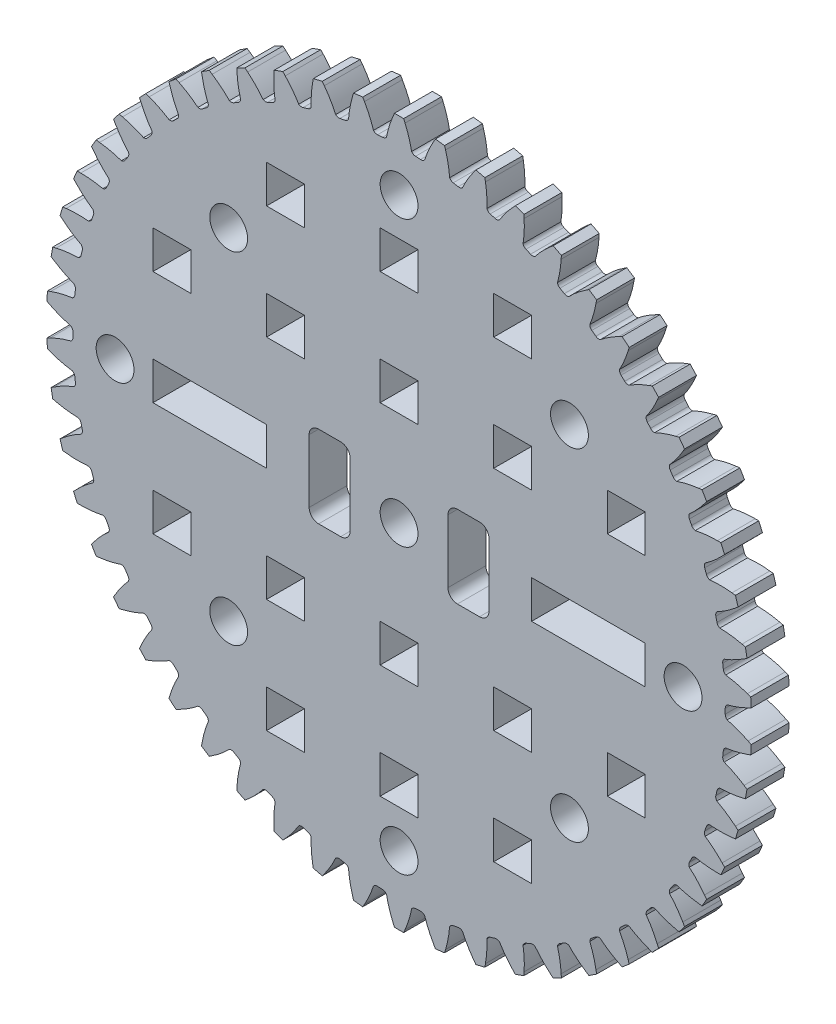
SolidWorks part; units mm, degrees
ref_plane "Alzado" through (0, 0, 0) normal (0, 0, 1) x (1, 0, 0)
ref_plane "Planta" through (0, 0, 0) normal (0, 1, 0) x (1, 0, 0)
ref_plane "Vista lateral" through (0, 0, 0) normal (1, 0, 0) x (0, 0, -1)
sketch "Model" plane through (0, 0, 0) normal (0, 0, 1) x (1, 0, 0)
  line L0 (26.2461, 285.5829) -> (26.2461, 282.5829)
  line L1 (29.2461, 285.5829) -> (26.2461, 285.5829)
  line L2 (29.2461, 282.5829) -> (29.2461, 285.5829)
  line L3 (26.2461, 282.5829) -> (29.2461, 282.5829)
  line L4 (35.2461, 285.5829) -> (35.2461, 282.5829)
  line L5 (38.2461, 285.5829) -> (35.2461, 285.5829)
  line L6 (38.2461, 282.5829) -> (38.2461, 285.5829)
  line L7 (35.2461, 282.5829) -> (38.2461, 282.5829)
  line L8 (44.2461, 285.5829) -> (44.2461, 282.5829)
  line L9 (47.2461, 285.5829) -> (44.2461, 285.5829)
  line L10 (47.2461, 282.5829) -> (47.2461, 285.5829)
  line L11 (44.2461, 282.5829) -> (47.2461, 282.5829)
  line L12 (56.2461, 258.5829) -> (53.2461, 258.5829)
  line L13 (56.2461, 255.5829) -> (56.2461, 258.5829)
  line L14 (53.2461, 255.5829) -> (56.2461, 255.5829)
  line L15 (53.2461, 258.5829) -> (53.2461, 255.5829)
  line L16 (56.2461, 276.5829) -> (53.2461, 276.5829)
  line L17 (56.2461, 273.5829) -> (56.2461, 276.5829)
  line L18 (53.2461, 273.5829) -> (56.2461, 273.5829)
  line L19 (53.2461, 276.5829) -> (53.2461, 273.5829)
  line L20 (47.2461, 267.5829) -> (47.2461, 264.5829)
  line L21 (26.2461, 276.5829) -> (26.2461, 273.5829)
  line L22 (29.2461, 276.5829) -> (26.2461, 276.5829)
  line L23 (29.2461, 273.5829) -> (29.2461, 276.5829)
  line L24 (26.2461, 273.5829) -> (29.2461, 273.5829)
  line L25 (35.2461, 276.5829) -> (35.2461, 273.5829)
  line L26 (38.2461, 276.5829) -> (35.2461, 276.5829)
  line L27 (38.2461, 273.5829) -> (38.2461, 276.5829)
  line L28 (35.2461, 273.5829) -> (38.2461, 273.5829)
  line L29 (44.2461, 276.5829) -> (44.2461, 273.5829)
  line L30 (47.2461, 276.5829) -> (44.2461, 276.5829)
  line L31 (47.2461, 273.5829) -> (47.2461, 276.5829)
  line L32 (44.2461, 273.5829) -> (47.2461, 273.5829)
  line L33 (26.2461, 258.5829) -> (26.2461, 255.5829)
  line L34 (29.2461, 258.5829) -> (26.2461, 258.5829)
  line L35 (29.2461, 255.5829) -> (29.2461, 258.5829)
  line L36 (26.2461, 255.5829) -> (29.2461, 255.5829)
  line L37 (35.2461, 258.5829) -> (35.2461, 255.5829)
  line L38 (38.2461, 258.5829) -> (35.2461, 258.5829)
  line L39 (38.2461, 255.5829) -> (38.2461, 258.5829)
  line L40 (35.2461, 255.5829) -> (38.2461, 255.5829)
  line L41 (44.2461, 258.5829) -> (44.2461, 255.5829)
  line L42 (47.2461, 258.5829) -> (44.2461, 258.5829)
  line L43 (47.2461, 255.5829) -> (47.2461, 258.5829)
  line L44 (44.2461, 255.5829) -> (47.2461, 255.5829)
  line L45 (26.2461, 249.5829) -> (26.2461, 246.5829)
  line L46 (29.2461, 249.5829) -> (26.2461, 249.5829)
  line L47 (29.2461, 246.5829) -> (29.2461, 249.5829)
  line L48 (26.2461, 246.5829) -> (29.2461, 246.5829)
  line L49 (35.2461, 249.5829) -> (35.2461, 246.5829)
  line L50 (38.2461, 249.5829) -> (35.2461, 249.5829)
  line L51 (38.2461, 246.5829) -> (38.2461, 249.5829)
  line L52 (35.2461, 246.5829) -> (38.2461, 246.5829)
  line L53 (44.2461, 249.5829) -> (44.2461, 246.5829)
  line L54 (47.2461, 249.5829) -> (44.2461, 249.5829)
  line L55 (47.2461, 246.5829) -> (47.2461, 249.5829)
  line L56 (44.2461, 246.5829) -> (47.2461, 246.5829)
  line L57 (20.2461, 258.5829) -> (17.2461, 258.5829)
  line L58 (20.2461, 255.5829) -> (20.2461, 258.5829)
  line L59 (17.2461, 255.5829) -> (20.2461, 255.5829)
  line L60 (17.2461, 258.5829) -> (17.2461, 255.5829)
  line L61 (20.2461, 276.5829) -> (17.2461, 276.5829)
  line L62 (20.2461, 273.5829) -> (20.2461, 276.5829)
  line L63 (17.2461, 273.5829) -> (20.2461, 273.5829)
  line L64 (17.2461, 276.5829) -> (17.2461, 273.5829)
  line L73 (56.2461, 267.5829) -> (47.2461, 267.5829)
  line L74 (56.2461, 264.5829) -> (56.2461, 267.5829)
  line L75 (47.2461, 264.5829) -> (56.2461, 264.5829)
  line L76 (17.2461, 267.5829) -> (17.2461, 264.5829)
  line L77 (26.2461, 267.5829) -> (17.2461, 267.5829)
  line L78 (26.2461, 264.5829) -> (26.2461, 267.5829)
  line L79 (17.2461, 264.5829) -> (26.2461, 264.5829)
  line L80 (43.1211, 269.3329) -> (41.3711, 269.3329)
  line L81 (43.8711, 263.5829) -> (43.8711, 268.5829)
  line L82 (41.3711, 262.8329) -> (43.1211, 262.8329)
  line L83 (40.6211, 268.5829) -> (40.6211, 263.5829)
  line L84 (30.3711, 269.3329) -> (32.1211, 269.3329)
  line L85 (29.6211, 263.5829) -> (29.6211, 268.5829)
  line L86 (32.1211, 262.8329) -> (30.3711, 262.8329)
  line L87 (32.8711, 268.5829) -> (32.8711, 263.5829)
  line L88 (42.6661, 293.1187) -> (42.8318, 293.3418)
  line L89 (42.8318, 293.3418) -> (43.5414, 293.1736)
  line L90 (43.5414, 293.1736) -> (43.5893, 292.8999)
  line L91 (43.967, 290.8966) -> (44.3484, 290.7824)
  line L92 (45.7647, 292.2486) -> (45.9552, 292.4509)
  line L93 (45.9552, 292.4509) -> (46.6405, 292.2015)
  line L94 (46.6405, 292.2015) -> (46.6563, 291.9241)
  line L95 (46.7989, 289.8905) -> (47.1644, 289.7328)
  line L96 (48.7414, 291.0247) -> (48.9541, 291.2035)
  line L97 (48.9541, 291.2035) -> (49.6058, 290.8762)
  line L98 (49.6058, 290.8762) -> (49.5893, 290.5988)
  line L99 (49.4948, 288.5625) -> (49.8396, 288.3634)
  line L100 (51.5559, 289.4634) -> (51.7879, 289.6164)
  line L101 (51.7879, 289.6164) -> (52.3971, 289.2157)
  line L102 (52.3971, 289.2157) -> (52.3486, 288.9421)
  line L103 (52.0183, 286.9304) -> (52.3376, 286.6927)
  line L104 (54.17, 287.586) -> (54.4182, 287.711)
  line L105 (54.4182, 287.711) -> (54.9769, 287.2423)
  line L106 (54.9769, 287.2423) -> (54.8969, 286.9762)
  line L107 (54.3353, 285.0165) -> (54.6249, 284.7433)
  line L108 (56.5486, 285.4178) -> (56.8096, 285.5132)
  line L109 (56.8096, 285.5132) -> (57.31, 284.9828)
  line L110 (57.31, 284.9828) -> (57.1997, 284.7277)
  line L111 (56.4144, 282.8465) -> (56.6703, 282.5415)
  line L112 (58.6593, 282.9882) -> (58.9297, 283.0526)
  line L113 (58.9297, 283.0526) -> (59.3651, 282.4676)
  line L114 (59.3651, 282.4676) -> (59.2259, 282.2271)
  line L115 (58.2276, 280.4497) -> (58.4463, 280.1172)
  line L116 (60.4738, 280.3299) -> (60.7497, 280.3624)
  line L117 (60.7497, 280.3624) -> (61.1143, 279.7309)
  line L118 (61.1143, 279.7309) -> (60.9482, 279.5082)
  line L119 (59.7502, 277.8588) -> (59.9289, 277.503)
  line L120 (61.9673, 277.4789) -> (62.2452, 277.4792)
  line L121 (62.2452, 277.4792) -> (62.534, 276.8097)
  line L122 (62.534, 276.8097) -> (62.3431, 276.6077)
  line L123 (60.9617, 275.1085) -> (61.0979, 274.7344)
  line L124 (63.1198, 274.4739) -> (63.3958, 274.4419)
  line L125 (63.3958, 274.4419) -> (63.6049, 273.7433)
  line L126 (63.6049, 273.7433) -> (63.3919, 273.5649)
  line L127 (61.8458, 272.2362) -> (61.9376, 271.8489)
  line L128 (63.9156, 271.3553) -> (64.186, 271.2916)
  line L129 (64.186, 271.2916) -> (64.3126, 270.5734)
  line L130 (64.3126, 270.5734) -> (64.0803, 270.421)
  line L131 (62.3905, 269.2807) -> (62.4367, 268.8853)
  line L132 (64.3439, 268.1655) -> (64.6052, 268.0707)
  line L133 (64.6052, 268.0707) -> (64.6476, 267.3428)
  line L134 (64.6476, 267.3428) -> (64.3991, 267.2183)
  line L135 (62.5883, 266.282) -> (62.5883, 265.8839)
  line L136 (64.3991, 264.9475) -> (64.6476, 264.8231)
  line L137 (64.6476, 264.8231) -> (64.6052, 264.0951)
  line L138 (64.6052, 264.0951) -> (64.3439, 264.0003)
  line L139 (62.4367, 263.2805) -> (62.3905, 262.8851)
  line L140 (64.0803, 261.7449) -> (64.3126, 261.5924)
  line L141 (64.3126, 261.5924) -> (64.186, 260.8743)
  line L142 (64.186, 260.8743) -> (63.9156, 260.8105)
  line L143 (61.9376, 260.317) -> (61.8458, 259.9296)
  line L144 (63.3919, 258.6009) -> (63.6049, 258.4225)
  line L145 (63.6049, 258.4225) -> (63.3958, 257.7239)
  line L146 (63.3958, 257.7239) -> (63.1198, 257.6919)
  line L147 (61.0979, 257.4314) -> (60.9617, 257.0573)
  line L148 (62.3431, 255.5581) -> (62.534, 255.3562)
  line L149 (62.534, 255.3562) -> (62.2452, 254.6866)
  line L150 (62.2452, 254.6866) -> (61.9673, 254.6869)
  line L151 (59.9289, 254.6628) -> (59.7502, 254.3071)
  line L152 (60.9482, 252.6576) -> (61.1143, 252.4349)
  line L153 (61.1143, 252.4349) -> (60.7497, 251.8034)
  line L154 (60.7497, 251.8034) -> (60.4738, 251.8359)
  line L155 (58.4463, 252.0487) -> (58.2276, 251.7161)
  line L156 (59.2259, 249.9387) -> (59.3651, 249.6982)
  line L157 (59.3651, 249.6982) -> (58.9297, 249.1133)
  line L158 (58.9297, 249.1133) -> (58.6593, 249.1776)
  line L159 (56.6703, 249.6243) -> (56.4144, 249.3194)
  line L160 (57.1997, 247.4381) -> (57.31, 247.1831)
  line L161 (57.31, 247.1831) -> (56.8096, 246.6527)
  line L162 (56.8096, 246.6527) -> (56.5486, 246.748)
  line L163 (54.6249, 247.4225) -> (54.3353, 247.1494)
  line L164 (54.8969, 245.1897) -> (54.9769, 244.9235)
  line L165 (54.9769, 244.9235) -> (54.4182, 244.4548)
  line L166 (54.4182, 244.4548) -> (54.17, 244.5798)
  line L167 (52.3376, 245.4731) -> (52.0183, 245.2354)
  line L168 (52.3486, 243.2238) -> (52.3971, 242.9501)
  line L169 (52.3971, 242.9501) -> (51.7879, 242.5494)
  line L170 (51.7879, 242.5494) -> (51.5559, 242.7024)
  line L171 (49.8396, 243.8024) -> (49.4948, 243.6034)
  line L172 (49.5893, 241.567) -> (49.6058, 241.2896)
  line L173 (49.6058, 241.2896) -> (48.9541, 240.9623)
  line L174 (48.9541, 240.9623) -> (48.7414, 241.1412)
  line L175 (47.1644, 242.433) -> (46.7989, 242.2753)
  line L176 (46.6563, 240.2417) -> (46.6405, 239.9643)
  line L177 (46.6405, 239.9643) -> (45.9552, 239.7149)
  line L178 (45.9552, 239.7149) -> (45.7647, 239.9172)
  line L179 (44.3484, 241.3834) -> (43.967, 241.2692)
  line L180 (43.5893, 239.266) -> (43.5414, 238.9922)
  line L181 (43.5414, 238.9922) -> (42.8318, 238.8241)
  line L182 (42.8318, 238.8241) -> (42.6661, 239.0471)
  line L183 (41.4295, 240.6678) -> (41.0375, 240.5987)
  line L184 (40.4298, 238.6528) -> (40.3504, 238.3865)
  line L185 (40.3504, 238.3865) -> (39.6261, 238.3019)
  line L186 (39.6261, 238.3019) -> (39.4874, 238.5427)
  line L187 (38.4474, 240.296) -> (38.05, 240.2728)
  line L188 (37.2205, 238.4106) -> (37.1107, 238.1554)
  line L189 (37.1107, 238.1554) -> (36.3815, 238.1554)
  line L190 (36.3815, 238.1554) -> (36.2717, 238.4106)
  line L191 (35.4422, 240.2728) -> (35.0448, 240.296)
  line L192 (34.0047, 238.5427) -> (33.866, 238.3019)
  line L193 (33.866, 238.3019) -> (33.1417, 238.3865)
  line L194 (33.1417, 238.3865) -> (33.0623, 238.6528)
  line L195 (32.4546, 240.5987) -> (32.0626, 240.6678)
  line L196 (30.826, 239.0471) -> (30.6603, 238.8241)
  line L197 (30.6603, 238.8241) -> (29.9507, 238.9922)
  line L198 (29.9507, 238.9922) -> (29.9028, 239.266)
  line L199 (29.5251, 241.2692) -> (29.1437, 241.3834)
  line L200 (27.7274, 239.9172) -> (27.5369, 239.7149)
  line L201 (27.5369, 239.7149) -> (26.8517, 239.9643)
  line L202 (26.8517, 239.9643) -> (26.8358, 240.2417)
  line L203 (26.6932, 242.2753) -> (26.3277, 242.433)
  line L204 (24.7507, 241.1412) -> (24.538, 240.9623)
  line L205 (24.538, 240.9623) -> (23.8864, 241.2896)
  line L206 (23.8864, 241.2896) -> (23.9028, 241.567)
  line L207 (23.9973, 243.6034) -> (23.6526, 243.8024)
  line L208 (21.9363, 242.7024) -> (21.7043, 242.5494)
  line L209 (21.7043, 242.5494) -> (21.095, 242.9501)
  line L210 (21.095, 242.9501) -> (21.1435, 243.2238)
  line L211 (19.3221, 244.5798) -> (19.0739, 244.4548)
  line L212 (19.0739, 244.4548) -> (18.5153, 244.9235)
  line L213 (18.5153, 244.9235) -> (18.5953, 245.1897)
  line L214 (19.1568, 247.1494) -> (18.8673, 247.4225)
  line L215 (16.9435, 246.748) -> (16.6825, 246.6527)
  line L216 (16.6825, 246.6527) -> (16.1821, 247.1831)
  line L217 (16.1821, 247.1831) -> (16.2924, 247.4381)
  line L218 (17.0777, 249.3194) -> (16.8218, 249.6243)
  line L219 (14.8328, 249.1776) -> (14.5625, 249.1133)
  line L220 (14.5625, 249.1133) -> (14.127, 249.6982)
  line L221 (14.127, 249.6982) -> (14.2662, 249.9387)
  line L222 (15.2646, 251.7161) -> (15.0458, 252.0487)
  line L223 (13.0184, 251.8359) -> (12.7424, 251.8034)
  line L224 (12.7424, 251.8034) -> (12.3778, 252.4349)
  line L225 (12.3778, 252.4349) -> (12.544, 252.6576)
  line L226 (13.7419, 254.3071) -> (13.5633, 254.6628)
  line L227 (11.5248, 254.6869) -> (11.2469, 254.6866)
  line L228 (11.2469, 254.6866) -> (10.9581, 255.3562)
  line L229 (10.9581, 255.3562) -> (11.149, 255.5581)
  line L230 (12.5304, 257.0573) -> (12.3942, 257.4314)
  line L231 (10.3724, 257.6919) -> (10.0963, 257.7239)
  line L232 (10.0963, 257.7239) -> (9.8872, 258.4225)
  line L233 (9.8872, 258.4225) -> (10.1003, 258.6009)
  line L234 (11.6463, 259.9296) -> (11.5545, 260.317)
  line L235 (9.5766, 260.8105) -> (9.3061, 260.8743)
  line L236 (9.3061, 260.8743) -> (9.1795, 261.5924)
  line L237 (9.1795, 261.5924) -> (9.4118, 261.7449)
  line L238 (11.1017, 262.8851) -> (11.0555, 263.2805)
  line L239 (9.1482, 264.0003) -> (8.887, 264.0951)
  line L240 (8.887, 264.0951) -> (8.8446, 264.8231)
  line L241 (8.8446, 264.8231) -> (9.093, 264.9475)
  line L242 (10.9038, 265.8839) -> (10.9038, 266.282)
  line L243 (9.093, 267.2183) -> (8.8446, 267.3428)
  line L244 (8.8446, 267.3428) -> (8.887, 268.0707)
  line L245 (8.887, 268.0707) -> (9.1482, 268.1655)
  line L246 (11.0555, 268.8853) -> (11.1017, 269.2807)
  line L247 (9.4118, 270.421) -> (9.1795, 270.5734)
  line L248 (9.1795, 270.5734) -> (9.3061, 271.2916)
  line L249 (9.3061, 271.2916) -> (9.5766, 271.3553)
  line L250 (11.5545, 271.8489) -> (11.6463, 272.2362)
  line L251 (10.1003, 273.5649) -> (9.8872, 273.7433)
  line L252 (9.8872, 273.7433) -> (10.0963, 274.4419)
  line L253 (10.0963, 274.4419) -> (10.3724, 274.4739)
  line L254 (12.3942, 274.7344) -> (12.5304, 275.1085)
  line L255 (11.149, 276.6077) -> (10.9581, 276.8097)
  line L256 (10.9581, 276.8097) -> (11.2469, 277.4792)
  line L257 (11.2469, 277.4792) -> (11.5248, 277.4789)
  line L258 (13.5633, 277.503) -> (13.7419, 277.8588)
  line L259 (12.544, 279.5082) -> (12.3778, 279.7309)
  line L260 (12.3778, 279.7309) -> (12.7424, 280.3624)
  line L261 (12.7424, 280.3624) -> (13.0184, 280.3299)
  line L262 (15.0458, 280.1172) -> (15.2646, 280.4497)
  line L263 (14.2662, 282.2271) -> (14.127, 282.4676)
  line L264 (14.127, 282.4676) -> (14.5625, 283.0526)
  line L265 (14.5625, 283.0526) -> (14.8328, 282.9882)
  line L266 (16.8218, 282.5415) -> (17.0777, 282.8465)
  line L267 (16.2924, 284.7277) -> (16.1821, 284.9828)
  line L268 (16.1821, 284.9828) -> (16.6825, 285.5132)
  line L269 (16.6825, 285.5132) -> (16.9435, 285.4178)
  line L270 (18.8673, 284.7433) -> (19.1568, 285.0165)
  line L271 (18.5953, 286.9762) -> (18.5153, 287.2423)
  line L272 (18.5153, 287.2423) -> (19.0739, 287.711)
  line L273 (19.0739, 287.711) -> (19.3221, 287.586)
  line L274 (21.1545, 286.6927) -> (21.4738, 286.9304)
  line L275 (21.1435, 288.9421) -> (21.095, 289.2157)
  line L276 (21.095, 289.2157) -> (21.7043, 289.6164)
  line L277 (21.7043, 289.6164) -> (21.9363, 289.4634)
  line L278 (23.6526, 288.3634) -> (23.9973, 288.5625)
  line L279 (23.9028, 290.5988) -> (23.8864, 290.8762)
  line L280 (23.8864, 290.8762) -> (24.538, 291.2035)
  line L281 (24.538, 291.2035) -> (24.7507, 291.0247)
  line L282 (26.3277, 289.7328) -> (26.6932, 289.8905)
  line L283 (26.8358, 291.9241) -> (26.8517, 292.2015)
  line L284 (26.8517, 292.2015) -> (27.5369, 292.4509)
  line L285 (27.5369, 292.4509) -> (27.7274, 292.2486)
  line L286 (29.1437, 290.7824) -> (29.5251, 290.8966)
  line L287 (29.9028, 292.8999) -> (29.9507, 293.1736)
  line L288 (29.9507, 293.1736) -> (30.6603, 293.3418)
  line L289 (30.6603, 293.3418) -> (30.826, 293.1187)
  line L290 (32.0626, 291.498) -> (32.4546, 291.5671)
  line L291 (33.0623, 293.513) -> (33.1417, 293.7793)
  line L292 (33.1417, 293.7793) -> (33.866, 293.864)
  line L293 (33.866, 293.864) -> (34.0047, 293.6231)
  line L294 (35.0448, 291.8699) -> (35.4422, 291.893)
  line L295 (38.05, 291.893) -> (38.4474, 291.8699)
  line L296 (39.4874, 293.6231) -> (39.6261, 293.864)
  line L297 (39.6261, 293.864) -> (40.3504, 293.7793)
  line L298 (40.3504, 293.7793) -> (40.4298, 293.513)
  line L299 (41.0375, 291.5671) -> (41.4295, 291.498)
  line L300 (21.1545, 245.4731) -> (21.4738, 245.2354)
  line L301 (36.2717, 293.7552) -> (36.3815, 294.0105)
  line L302 (36.3815, 294.0105) -> (37.1107, 294.0105)
  line L303 (37.1107, 294.0105) -> (37.2205, 293.7552)
  circle A0 centre (36.7461, 288.5829) radius 1.5
  arc A1 (41.3711, 269.3329) -> (40.6211, 268.5829) centre (41.3711, 268.5829) ccw
  arc A2 (43.8711, 268.5829) -> (43.1211, 269.3329) centre (43.1211, 268.5829) ccw
  arc A3 (43.1211, 262.8329) -> (43.8711, 263.5829) centre (43.1211, 263.5829) ccw
  arc A4 (40.6211, 263.5829) -> (41.3711, 262.8329) centre (41.3711, 263.5829) ccw
  arc A5 (32.8711, 268.5829) -> (32.1211, 269.3329) centre (32.1211, 268.5829) ccw
  arc A6 (30.3711, 269.3329) -> (29.6211, 268.5829) centre (30.3711, 268.5829) ccw
  arc A7 (29.6211, 263.5829) -> (30.3711, 262.8329) centre (30.3711, 263.5829) ccw
  arc A8 (32.1211, 262.8329) -> (32.8711, 263.5829) centre (32.1211, 263.5829) ccw
  circle A9 centre (50.2461, 279.5829) radius 1.5
  circle A10 centre (50.2461, 252.5829) radius 1.5
  circle A11 centre (23.2461, 279.5829) radius 1.5
  circle A12 centre (23.2461, 252.5829) radius 1.5
  circle A13 centre (36.7461, 266.0829) radius 1.5
  circle A14 centre (14.2461, 266.0829) radius 1.5
  circle A15 centre (59.2461, 266.0829) radius 1.5
  circle A16 centre (36.7461, 243.5829) radius 1.5
  arc A17 (41.4295, 291.498) -> (41.7683, 291.5932) centre (41.5054, 291.8781) ccw
  arc A18 (42.6661, 293.1187) -> (41.7683, 291.5932) centre (49.3335, 288.1676) ccw
  arc A19 (43.707, 291.1338) -> (43.5893, 292.8999) centre (35.4091, 291.4678) ccw
  arc A20 (43.707, 291.1338) -> (43.967, 290.8966) centre (44.0698, 291.2703) ccw
  arc A21 (44.3484, 290.7824) -> (44.6959, 290.8377) centre (44.4679, 291.1511) ccw
  arc A22 (45.7647, 292.2486) -> (44.6959, 290.8377) centre (51.8123, 286.557) ccw
  arc A23 (46.5682, 290.1563) -> (46.6563, 291.9241) centre (38.3651, 291.4513) ccw
  arc A24 (46.5682, 290.1563) -> (46.7989, 289.8905) centre (46.9443, 290.2498) ccw
  arc A25 (47.1644, 289.7328) -> (47.516, 289.7474) centre (47.3259, 290.0852) ccw
  arc A26 (48.7414, 291.0247) -> (47.516, 289.7474) centre (54.0873, 284.6694) ccw
  arc A27 (49.2965, 288.8532) -> (49.5893, 290.5988) centre (41.2993, 291.0919) ccw
  arc A28 (49.2965, 288.8532) -> (49.4948, 288.5625) centre (49.681, 288.9024) ccw
  arc A29 (49.8396, 288.3634) -> (50.1905, 288.3371) centre (50.0409, 288.6946) ccw
  arc A30 (51.5559, 289.4634) -> (50.1905, 288.3371) centre (56.1278, 282.5306) ccw
  arc A31 (51.8551, 287.2422) -> (52.3486, 288.9421) centre (44.1718, 290.3942) ccw
  arc A32 (51.8551, 287.2422) -> (52.0183, 286.9304) centre (52.2427, 287.2465) ccw
  arc A33 (52.3376, 286.6927) -> (52.6831, 286.6258) centre (52.576, 286.9983) ccw
  arc A34 (54.17, 287.586) -> (52.6831, 286.6258) centre (57.9062, 280.1693) ccw
  arc A35 (54.2094, 285.3451) -> (54.8969, 286.9762) centre (46.944, 289.3677) ccw
  arc A36 (54.2094, 285.3451) -> (54.3353, 285.0165) centre (54.5948, 285.3043) ccw
  arc A37 (54.6249, 284.7433) -> (54.9602, 284.6367) centre (54.8971, 285.0191) ccw
  arc A38 (56.5486, 285.4178) -> (54.9602, 284.6367) centre (59.3985, 277.6175) ccw
  arc A39 (56.3275, 283.1875) -> (57.1997, 284.7277) centre (49.5782, 288.0263) ccw
  arc A40 (56.3275, 283.1875) -> (56.4144, 282.8465) centre (56.7056, 283.1022) ccw
  arc A41 (56.6703, 282.5415) -> (56.9911, 282.3967) centre (56.9728, 282.7839) ccw
  arc A42 (58.6593, 282.9882) -> (56.9911, 282.3967) centre (60.5844, 274.9097) ccw
  arc A43 (58.1809, 280.7985) -> (59.2259, 282.2271) centre (52.0389, 286.3882) ccw
  arc A44 (58.1809, 280.7985) -> (58.2276, 280.4497) centre (58.5465, 280.67) ccw
  arc A45 (58.4463, 280.1172) -> (58.7481, 279.9361) centre (58.7749, 280.3228) ccw
  arc A46 (60.4738, 280.3299) -> (58.7481, 279.9361) centre (61.4479, 272.0826) ccw
  arc A47 (59.7443, 278.2106) -> (60.9482, 279.5082) centre (54.2928, 284.4755) ccw
  arc A48 (59.7443, 278.2106) -> (59.7502, 277.8588) centre (60.0925, 278.0405) ccw
  arc A49 (59.9289, 277.503) -> (60.2076, 277.2882) centre (60.279, 277.6691) ccw
  arc A50 (61.9673, 277.4789) -> (60.2076, 277.2882) centre (61.9774, 269.1743) ccw
  arc A51 (60.9967, 275.4587) -> (62.3431, 276.6077) centre (56.3095, 282.3141) ccw
  arc A52 (60.9967, 275.4587) -> (60.9617, 275.1085) centre (61.3229, 275.2493) ccw
  arc A53 (61.0979, 274.7344) -> (61.3498, 274.4887) centre (61.465, 274.8587) ccw
  arc A54 (63.1198, 274.4739) -> (61.3498, 274.4887) centre (62.1657, 266.2242) ccw
  arc A55 (61.9212, 272.58) -> (63.3919, 273.5649) centre (58.0615, 279.9332) ccw
  arc A56 (61.9212, 272.58) -> (61.8458, 272.2362) centre (62.2208, 272.3341) ccw
  arc A57 (61.9376, 271.8489) -> (62.1593, 271.5755) centre (62.3167, 271.9297) ccw
  arc A58 (63.9156, 271.3553) -> (62.1593, 271.5755) centre (62.0102, 263.2722) ccw
  arc A59 (62.5053, 269.6134) -> (64.0803, 270.421) centre (59.5253, 277.365) ccw
  arc A60 (62.5053, 269.6134) -> (62.3905, 269.2807) centre (62.7743, 269.3344) ccw
  arc A61 (62.4367, 268.8853) -> (62.6251, 268.5881) centre (62.8225, 268.9216) ccw
  arc A62 (64.3439, 268.1655) -> (62.6251, 268.5881) centre (61.5131, 260.3582) ccw
  arc A63 (62.7409, 266.599) -> (64.3991, 267.2183) centre (60.681, 274.6442) ccw
  arc A64 (62.7409, 266.599) -> (62.5883, 266.282) centre (62.9758, 266.2907) ccw
  arc A65 (62.5883, 265.8839) -> (62.7409, 265.5668) centre (62.9758, 265.8751) ccw
  arc A66 (64.3991, 264.9475) -> (62.7409, 265.5668) centre (60.681, 257.5216) ccw
  arc A67 (62.6251, 263.5777) -> (64.3439, 264.0003) centre (61.5131, 271.8076) ccw
  arc A68 (62.6251, 263.5777) -> (62.4367, 263.2805) centre (62.8225, 263.2442) ccw
  arc A69 (62.3905, 262.8851) -> (62.5053, 262.5525) centre (62.7743, 262.8314) ccw
  arc A70 (64.0803, 261.7449) -> (62.5053, 262.5525) centre (59.5253, 254.8008) ccw
  arc A71 (62.1593, 260.5903) -> (63.9156, 260.8105) centre (62.0102, 268.8936) ccw
  arc A72 (62.1593, 260.5903) -> (61.9376, 260.317) centre (62.3167, 260.2361) ccw
  arc A73 (61.8458, 259.9296) -> (61.9212, 259.5859) centre (62.2208, 259.8317) ccw
  arc A74 (63.3919, 258.6009) -> (61.9212, 259.5859) centre (58.0615, 252.2326) ccw
  arc A75 (61.3498, 257.6771) -> (63.1198, 257.6919) centre (62.1657, 265.9416) ccw
  arc A76 (61.3498, 257.6771) -> (61.0979, 257.4314) centre (61.465, 257.3071) ccw
  arc A77 (60.9617, 257.0573) -> (60.9967, 256.7071) centre (61.3229, 256.9166) ccw
  arc A78 (62.3431, 255.5581) -> (60.9967, 256.7071) centre (56.3095, 249.8517) ccw
  arc A79 (60.2076, 254.8777) -> (61.9673, 254.6869) centre (61.9774, 262.9915) ccw
  arc A80 (60.2076, 254.8777) -> (59.9289, 254.6628) centre (60.279, 254.4967) ccw
  arc A81 (59.7502, 254.3071) -> (59.7443, 253.9552) centre (60.0925, 254.1253) ccw
  arc A82 (60.9482, 252.6576) -> (59.7443, 253.9552) centre (54.2928, 247.6903) ccw
  arc A83 (58.7481, 252.2297) -> (60.4738, 251.8359) centre (61.4479, 260.0833) ccw
  arc A84 (58.7481, 252.2297) -> (58.4463, 252.0487) centre (58.7749, 251.8431) ccw
  arc A85 (58.2276, 251.7161) -> (58.1809, 251.3673) centre (58.5465, 251.4958) ccw
  arc A86 (59.2259, 249.9387) -> (58.1809, 251.3673) centre (52.0389, 245.7776) ccw
  arc A87 (56.9911, 249.7691) -> (58.6593, 249.1776) centre (60.5844, 257.2561) ccw
  arc A88 (56.9911, 249.7691) -> (56.6703, 249.6243) centre (56.9728, 249.382) ccw
  arc A89 (56.4144, 249.3194) -> (56.3275, 248.9784) centre (56.7056, 249.0636) ccw
  arc A90 (57.1997, 247.4381) -> (56.3275, 248.9784) centre (49.5782, 244.1395) ccw
  arc A91 (54.9602, 247.5291) -> (56.5486, 246.748) centre (59.3985, 254.5483) ccw
  arc A92 (54.9602, 247.5291) -> (54.6249, 247.4225) centre (54.8971, 247.1467) ccw
  arc A93 (54.3353, 247.1494) -> (54.2094, 246.8207) centre (54.5948, 246.8615) ccw
  arc A94 (54.8969, 245.1897) -> (54.2094, 246.8207) centre (46.944, 242.7981) ccw
  arc A95 (52.6831, 245.54) -> (54.17, 244.5798) centre (57.9062, 251.9965) ccw
  arc A96 (52.6831, 245.54) -> (52.3376, 245.4731) centre (52.576, 245.1675) ccw
  arc A97 (52.0183, 245.2354) -> (51.8551, 244.9236) centre (52.2427, 244.9194) ccw
  arc A98 (52.3486, 243.2238) -> (51.8551, 244.9236) centre (44.1718, 241.7717) ccw
  arc A99 (50.1905, 243.8287) -> (51.5559, 242.7024) centre (56.1278, 249.6352) ccw
  arc A100 (50.1905, 243.8287) -> (49.8396, 243.8024) centre (50.0409, 243.4712) ccw
  arc A101 (49.4948, 243.6034) -> (49.2965, 243.3126) centre (49.681, 243.2634) ccw
  arc A102 (49.5893, 241.567) -> (49.2965, 243.3126) centre (41.2993, 241.074) ccw
  arc A103 (47.516, 242.4184) -> (48.7414, 241.1412) centre (54.0873, 247.4964) ccw
  arc A104 (47.516, 242.4184) -> (47.1644, 242.433) centre (47.3259, 242.0807) ccw
  arc A105 (46.7989, 242.2753) -> (46.5682, 242.0096) centre (46.9443, 241.9161) ccw
  arc A106 (46.6563, 240.2417) -> (46.5682, 242.0096) centre (38.3651, 240.7145) ccw
  arc A107 (44.6959, 241.3281) -> (45.7647, 239.9172) centre (51.8123, 245.6089) ccw
  arc A108 (44.6959, 241.3281) -> (44.3484, 241.3834) centre (44.4679, 241.0147) ccw
  arc A109 (43.967, 241.2692) -> (43.707, 241.0321) centre (44.0698, 240.8955) ccw
  arc A110 (43.5893, 239.266) -> (43.707, 241.0321) centre (35.4091, 240.698) ccw
  arc A111 (41.7683, 240.5726) -> (42.6661, 239.0471) centre (49.3335, 243.9982) ccw
  arc A112 (41.7683, 240.5726) -> (41.4295, 240.6678) centre (41.5054, 240.2878) ccw
  arc A113 (41.0375, 240.5987) -> (40.7517, 240.3933) centre (41.0962, 240.2156) ccw
  arc A114 (40.4298, 238.6528) -> (40.7517, 240.3933) centre (32.4711, 241.0249) ccw
  arc A115 (38.7728, 240.162) -> (39.4874, 238.5427) centre (46.6846, 242.6862) ccw
  arc A116 (38.7728, 240.162) -> (38.4474, 240.296) centre (38.4786, 239.9097) ccw
  arc A117 (38.05, 240.2728) -> (37.7423, 240.102) centre (38.0637, 239.8855) ccw
  arc A118 (37.2205, 238.4106) -> (37.7423, 240.102) centre (29.591, 241.6906) ccw
  arc A119 (35.7498, 240.102) -> (36.2717, 238.4106) centre (43.9012, 241.6906) ccw
  arc A120 (35.7498, 240.102) -> (35.4422, 240.2728) centre (35.4284, 239.8855) ccw
  arc A121 (35.0448, 240.296) -> (34.7193, 240.162) centre (35.0135, 239.9097) ccw
  arc A122 (34.0047, 238.5427) -> (34.7193, 240.162) centre (26.8076, 242.6862) ccw
  arc A123 (32.7404, 240.3933) -> (33.0623, 238.6528) centre (41.021, 241.0249) ccw
  arc A124 (32.7404, 240.3933) -> (32.4546, 240.5987) centre (32.396, 240.2156) ccw
  arc A125 (32.0626, 240.6678) -> (31.7238, 240.5726) centre (31.9867, 240.2878) ccw
  arc A126 (30.826, 239.0471) -> (31.7238, 240.5726) centre (24.1586, 243.9982) ccw
  arc A127 (29.7851, 241.0321) -> (29.9028, 239.266) centre (38.083, 240.698) ccw
  arc A128 (29.7851, 241.0321) -> (29.5251, 241.2692) centre (29.4224, 240.8955) ccw
  arc A129 (29.1437, 241.3834) -> (28.7962, 241.3281) centre (29.0242, 241.0147) ccw
  arc A130 (27.7274, 239.9172) -> (28.7962, 241.3281) centre (21.6798, 245.6089) ccw
  arc A131 (26.9239, 242.0096) -> (26.8358, 240.2417) centre (35.127, 240.7145) ccw
  arc A132 (26.9239, 242.0096) -> (26.6932, 242.2753) centre (26.5478, 241.9161) ccw
  arc A133 (26.3277, 242.433) -> (25.9761, 242.4184) centre (26.1662, 242.0807) ccw
  arc A134 (24.7507, 241.1412) -> (25.9761, 242.4184) centre (19.4048, 247.4964) ccw
  arc A135 (24.1956, 243.3126) -> (23.9028, 241.567) centre (32.1929, 241.074) ccw
  arc A136 (24.1956, 243.3126) -> (23.9973, 243.6034) centre (23.8112, 243.2634) ccw
  arc A137 (23.6526, 243.8024) -> (23.3016, 243.8287) centre (23.4513, 243.4712) ccw
  arc A138 (21.9363, 242.7024) -> (23.3016, 243.8287) centre (17.3643, 249.6352) ccw
  arc A139 (21.637, 244.9236) -> (21.1435, 243.2238) centre (29.3203, 241.7717) ccw
  arc A140 (21.637, 244.9236) -> (21.4738, 245.2354) centre (21.2494, 244.9194) ccw
  arc A141 (19.3221, 244.5798) -> (20.809, 245.54) centre (15.5859, 251.9965) ccw
  arc A142 (19.2827, 246.8207) -> (18.5953, 245.1897) centre (26.5481, 242.7981) ccw
  arc A143 (18.8673, 247.4225) -> (18.5319, 247.5291) centre (18.595, 247.1467) ccw
  arc A144 (16.9435, 246.748) -> (18.5319, 247.5291) centre (14.0936, 254.5483) ccw
  arc A145 (17.1646, 248.9784) -> (16.2924, 247.4381) centre (23.9139, 244.1395) ccw
  arc A146 (17.1646, 248.9784) -> (17.0777, 249.3194) centre (16.7865, 249.0636) ccw
  arc A147 (16.8218, 249.6243) -> (16.5011, 249.7691) centre (16.5194, 249.382) ccw
  arc A148 (14.8328, 249.1776) -> (16.5011, 249.7691) centre (12.9077, 257.2561) ccw
  arc A149 (15.3113, 251.3673) -> (14.2662, 249.9387) centre (21.4532, 245.7776) ccw
  arc A150 (15.3113, 251.3673) -> (15.2646, 251.7161) centre (14.9456, 251.4958) ccw
  arc A151 (15.0458, 252.0487) -> (14.744, 252.2297) centre (14.7173, 251.8431) ccw
  arc A152 (13.0184, 251.8359) -> (14.744, 252.2297) centre (12.0442, 260.0833) ccw
  arc A153 (13.7478, 253.9552) -> (12.544, 252.6576) centre (19.1993, 247.6903) ccw
  arc A154 (13.7478, 253.9552) -> (13.7419, 254.3071) centre (13.3996, 254.1253) ccw
  arc A155 (13.5633, 254.6628) -> (13.2846, 254.8777) centre (13.2131, 254.4967) ccw
  arc A156 (11.5248, 254.6869) -> (13.2846, 254.8777) centre (11.5147, 262.9915) ccw
  arc A157 (12.4954, 256.7071) -> (11.149, 255.5581) centre (17.1827, 249.8517) ccw
  arc A158 (12.4954, 256.7071) -> (12.5304, 257.0573) centre (12.1693, 256.9166) ccw
  arc A159 (12.3942, 257.4314) -> (12.1423, 257.6771) centre (12.0271, 257.3071) ccw
  arc A160 (10.3724, 257.6919) -> (12.1423, 257.6771) centre (11.3264, 265.9416) ccw
  arc A161 (11.5709, 259.5859) -> (10.1003, 258.6009) centre (15.4306, 252.2326) ccw
  arc A162 (11.5709, 259.5859) -> (11.6463, 259.9296) centre (11.2713, 259.8317) ccw
  arc A163 (11.5545, 260.317) -> (11.3329, 260.5903) centre (11.1755, 260.2361) ccw
  arc A164 (9.5766, 260.8105) -> (11.3329, 260.5903) centre (11.4819, 268.8936) ccw
  arc A165 (10.9869, 262.5525) -> (9.4118, 261.7449) centre (13.9668, 254.8008) ccw
  arc A166 (10.9869, 262.5525) -> (11.1017, 262.8851) centre (10.7178, 262.8314) ccw
  arc A167 (11.0555, 263.2805) -> (10.867, 263.5777) centre (10.6696, 263.2442) ccw
  arc A168 (9.1482, 264.0003) -> (10.867, 263.5777) centre (11.979, 271.8076) ccw
  arc A169 (10.7512, 265.5668) -> (9.093, 264.9475) centre (12.8111, 257.5216) ccw
  arc A170 (10.7512, 265.5668) -> (10.9038, 265.8839) centre (10.5164, 265.8751) ccw
  arc A171 (10.9038, 266.282) -> (10.7512, 266.599) centre (10.5164, 266.2907) ccw
  arc A172 (9.093, 267.2183) -> (10.7512, 266.599) centre (12.8111, 274.6442) ccw
  arc A173 (10.867, 268.5881) -> (9.1482, 268.1655) centre (11.979, 260.3582) ccw
  arc A174 (10.867, 268.5881) -> (11.0555, 268.8853) centre (10.6696, 268.9216) ccw
  arc A175 (11.1017, 269.2807) -> (10.9869, 269.6134) centre (10.7178, 269.3344) ccw
  arc A176 (9.4118, 270.421) -> (10.9869, 269.6134) centre (13.9668, 277.365) ccw
  arc A177 (11.3329, 271.5755) -> (9.5766, 271.3553) centre (11.4819, 263.2722) ccw
  arc A178 (11.3329, 271.5755) -> (11.5545, 271.8489) centre (11.1755, 271.9297) ccw
  arc A179 (11.6463, 272.2362) -> (11.5709, 272.58) centre (11.2713, 272.3341) ccw
  arc A180 (10.1003, 273.5649) -> (11.5709, 272.58) centre (15.4306, 279.9332) ccw
  arc A181 (12.1423, 274.4887) -> (10.3724, 274.4739) centre (11.3264, 266.2242) ccw
  arc A182 (12.1423, 274.4887) -> (12.3942, 274.7344) centre (12.0271, 274.8587) ccw
  arc A183 (12.5304, 275.1085) -> (12.4954, 275.4587) centre (12.1693, 275.2493) ccw
  arc A184 (11.149, 276.6077) -> (12.4954, 275.4587) centre (17.1827, 282.3141) ccw
  arc A185 (13.2846, 277.2882) -> (11.5248, 277.4789) centre (11.5147, 269.1743) ccw
  arc A186 (13.2846, 277.2882) -> (13.5633, 277.503) centre (13.2131, 277.6691) ccw
  arc A187 (13.7419, 277.8588) -> (13.7478, 278.2106) centre (13.3996, 278.0405) ccw
  arc A188 (12.544, 279.5082) -> (13.7478, 278.2106) centre (19.1993, 284.4755) ccw
  arc A189 (14.744, 279.9361) -> (13.0184, 280.3299) centre (12.0442, 272.0826) ccw
  arc A190 (14.744, 279.9361) -> (15.0458, 280.1172) centre (14.7173, 280.3228) ccw
  arc A191 (15.2646, 280.4497) -> (15.3113, 280.7985) centre (14.9456, 280.67) ccw
  arc A192 (14.2662, 282.2271) -> (15.3113, 280.7985) centre (21.4532, 286.3882) ccw
  arc A193 (16.5011, 282.3967) -> (14.8328, 282.9882) centre (12.9077, 274.9097) ccw
  arc A194 (16.5011, 282.3967) -> (16.8218, 282.5415) centre (16.5194, 282.7839) ccw
  arc A195 (17.0777, 282.8465) -> (17.1646, 283.1875) centre (16.7865, 283.1022) ccw
  arc A196 (16.2924, 284.7277) -> (17.1646, 283.1875) centre (23.9139, 288.0263) ccw
  arc A197 (18.5319, 284.6367) -> (16.9435, 285.4178) centre (14.0936, 277.6175) ccw
  arc A198 (18.5319, 284.6367) -> (18.8673, 284.7433) centre (18.595, 285.0191) ccw
  arc A199 (19.1568, 285.0165) -> (19.2827, 285.3451) centre (18.8973, 285.3043) ccw
  arc A200 (18.5953, 286.9762) -> (19.2827, 285.3451) centre (26.5481, 289.3677) ccw
  arc A201 (20.809, 286.6258) -> (19.3221, 287.586) centre (15.5859, 280.1693) ccw
  arc A202 (20.809, 286.6258) -> (21.1545, 286.6927) centre (20.9161, 286.9983) ccw
  arc A203 (21.4738, 286.9304) -> (21.637, 287.2422) centre (21.2494, 287.2465) ccw
  arc A204 (21.1435, 288.9421) -> (21.637, 287.2422) centre (29.3203, 290.3942) ccw
  arc A205 (23.3016, 288.3371) -> (21.9363, 289.4634) centre (17.3643, 282.5306) ccw
  arc A206 (23.3016, 288.3371) -> (23.6526, 288.3634) centre (23.4513, 288.6946) ccw
  arc A207 (23.9973, 288.5625) -> (24.1956, 288.8532) centre (23.8112, 288.9024) ccw
  arc A208 (23.9028, 290.5988) -> (24.1956, 288.8532) centre (32.1929, 291.0919) ccw
  arc A209 (25.9761, 289.7474) -> (24.7507, 291.0247) centre (19.4048, 284.6694) ccw
  arc A210 (25.9761, 289.7474) -> (26.3277, 289.7328) centre (26.1662, 290.0852) ccw
  arc A211 (26.6932, 289.8905) -> (26.9239, 290.1563) centre (26.5478, 290.2498) ccw
  arc A212 (26.8358, 291.9241) -> (26.9239, 290.1563) centre (35.127, 291.4513) ccw
  arc A213 (28.7962, 290.8377) -> (27.7274, 292.2486) centre (21.6798, 286.557) ccw
  arc A214 (28.7962, 290.8377) -> (29.1437, 290.7824) centre (29.0242, 291.1511) ccw
  arc A215 (29.5251, 290.8966) -> (29.7851, 291.1338) centre (29.4224, 291.2703) ccw
  arc A216 (29.9028, 292.8999) -> (29.7851, 291.1338) centre (38.083, 291.4678) ccw
  arc A217 (31.7238, 291.5932) -> (30.826, 293.1187) centre (24.1586, 288.1676) ccw
  arc A218 (31.7238, 291.5932) -> (32.0626, 291.498) centre (31.9867, 291.8781) ccw
  arc A219 (32.4546, 291.5671) -> (32.7404, 291.7725) centre (32.396, 291.9502) ccw
  arc A220 (33.0623, 293.513) -> (32.7404, 291.7725) centre (41.021, 291.1409) ccw
  arc A221 (34.7193, 292.0038) -> (34.0047, 293.6231) centre (26.8076, 289.4796) ccw
  arc A222 (34.7193, 292.0038) -> (35.0448, 291.8699) centre (35.0135, 292.2562) ccw
  arc A223 (21.1545, 245.4731) -> (20.809, 245.54) centre (20.9161, 245.1675) ccw
  arc A224 (19.2827, 246.8207) -> (19.1568, 247.1494) centre (18.8973, 246.8615) ccw
  arc A225 (38.4474, 291.8699) -> (38.7728, 292.0038) centre (38.4786, 292.2562) ccw
  arc A226 (39.4874, 293.6231) -> (38.7728, 292.0038) centre (46.6846, 289.4796) ccw
  arc A227 (40.7517, 291.7725) -> (40.4298, 293.513) centre (32.4711, 291.1409) ccw
  arc A228 (40.7517, 291.7725) -> (41.0375, 291.5671) centre (41.0962, 291.9502) ccw
  arc A229 (35.4422, 291.893) -> (35.7498, 292.0638) centre (35.4284, 292.2803) ccw
  arc A230 (36.2717, 293.7552) -> (35.7498, 292.0638) centre (43.9012, 290.4752) ccw
  arc A231 (37.7423, 292.0638) -> (37.2205, 293.7552) centre (29.591, 290.4752) ccw
  arc A232 (37.7423, 292.0638) -> (38.05, 291.893) centre (38.0637, 292.2803) ccw
extrude "Saliente-Extruir1" add sketch "Model" along normal blind 3
